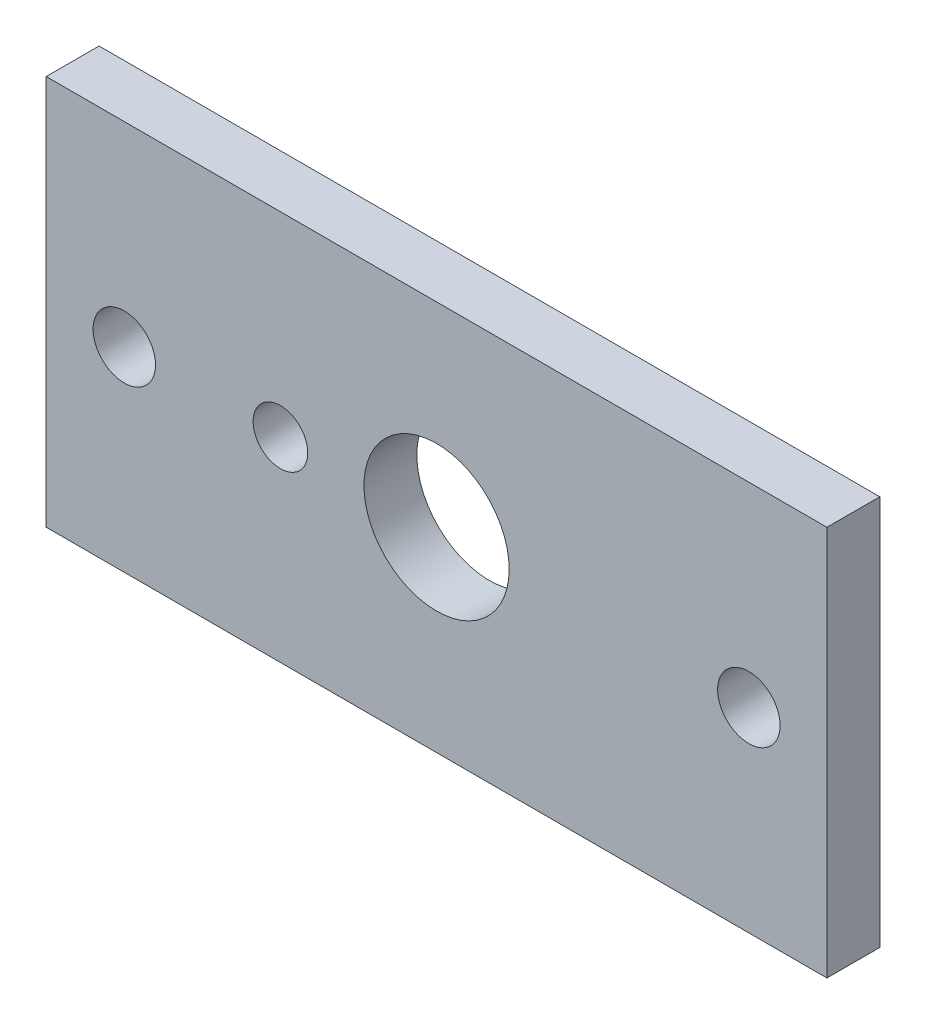
SolidWorks part; units mm, degrees
ref_plane "Front Plane" through (0, 0, 0) normal (0, 0, 1) x (1, 0, 0)
ref_plane "Top Plane" through (0, 0, 0) normal (0, 1, 0) x (1, 0, 0)
ref_plane "Right Plane" through (0, 0, 0) normal (1, 0, 0) x (0, 0, -1)
sketch "Sketch1" plane through (0, 0, 0) normal (0, 0, 1) x (1, 0, 0)
  line L1 (-25, 12.5) -> (25, 12.5)
  line L2 (-25, 12.5) -> (-25, -12.5)
  line L3 (-25, -12.5) -> (25, -12.5)
  line L4 (25, 12.5) -> (25, -12.5)
  line L5 (-25, 12.5) -> (25, -12.5) construction
  line L6 (-25, -12.5) -> (25, 12.5) construction
  circle A0 centre (0, 0) radius 4.65
  circle A1 centre (-10, 0) radius 1.75
  circle A2 centre (20, 0) radius 2
  circle A3 centre (-20, 0) radius 2
  point P0 (0, 0)
  dimension "D3" = 9.3
  dimension "D4" = 3.5
  dimension "D6" = 20
  dimension "D7" = 20
  dimension "D8" = 4
  dimension "D9" = 4
  dimension "D1" = 25
  dimension "D2" = 50
  dimension "D5" = 10
extrude "Boss-Extrude1" add sketch "Sketch1" along normal blind 3.385
equation "\"3.385nn\"=3"
